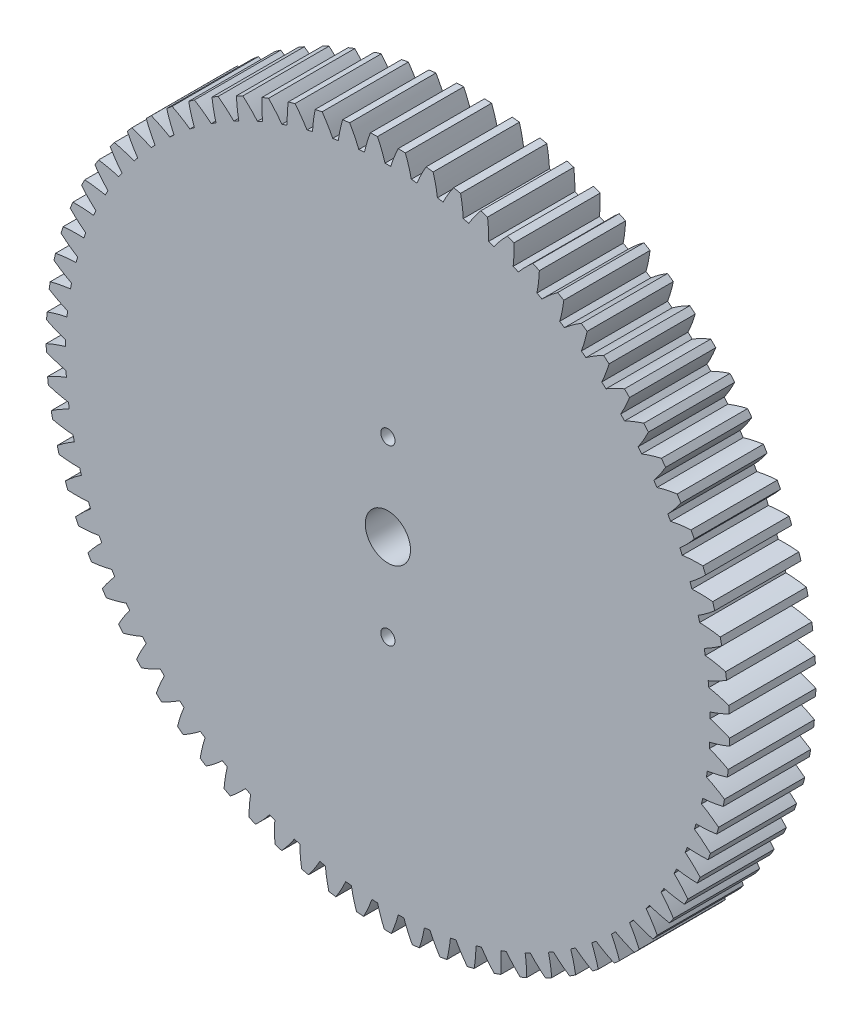
SolidWorks part; units mm, degrees
ref_plane "Front Plane" through (0, 0, 0) normal (0, 0, 1) x (1, 0, 0)
ref_plane "Top Plane" through (0, 0, 0) normal (0, 1, 0) x (1, 0, 0)
ref_plane "Right Plane" through (0, 0, 0) normal (1, 0, 0) x (0, 0, -1)
sketch "Model" plane through (0, 0, 0) normal (0, 0, 1) x (1, 0, 0)
  circle A3 centre (0, 0) radius 2.625
  circle A4 centre (0, 10.05) radius 0.825
  circle A5 centre (0, -10.05) radius 0.825
  arc A311 (-39.5739, 2.0126) -> (-37.3581, 1.0914) centre (-32.524, 15.8446) ccw
  arc A312 (-37.3581, 1.0914) -> (-37.3715, 0.4333) centre (0, 0) ccw
  arc A313 (-37.3715, 0.4333) -> (-39.623, -0.3968) centre (-33.1432, -14.5048) ccw
  arc A314 (-39.623, -0.3968) -> (-39.6062, -1.2197) centre (0, 0) ccw
  arc A315 (-39.6062, -1.2197) -> (-37.3227, -1.9572) centre (-33.7072, 13.1409) ccw
  arc A316 (-37.3227, -1.9572) -> (-37.2825, -2.6143) centre (0, 0) ccw
  arc A317 (-37.2825, -2.6143) -> (-39.4588, -3.6251) centre (-31.8506, -17.158) ccw
  arc A318 (-39.4588, -3.6251) -> (-39.375, -4.4439) centre (0, 0) ccw
  arc A319 (-39.375, -4.4439) -> (-37.039, -4.9929) centre (-34.6662, 10.3497) ccw
  arc A320 (-37.039, -4.9929) -> (-36.9453, -5.6445) centre (0, 0) ccw
  arc A321 (-36.9453, -5.6445) -> (-39.0321, -6.8293) centre (-30.3461, -19.6971) ccw
  arc A322 (-39.0321, -6.8293) -> (-38.8818, -7.6386) centre (0, 0) ccw
  arc A323 (-38.8818, -7.6386) -> (-36.5088, -7.9953) centre (-35.3944, 7.4897) ccw
  arc A324 (-36.5088, -7.9953) -> (-36.3623, -8.6371) centre (0, 0) ccw
  arc A325 (-36.3623, -8.6371) -> (-38.3455, -9.988) centre (-28.6396, -22.105) ccw
  arc A326 (-38.3455, -9.988) -> (-38.1298, -10.7824) centre (0, 0) ccw
  arc A327 (-38.1298, -10.7824) -> (-35.7356, -10.9445) centre (-35.8871, 4.5798) ccw
  arc A328 (-35.7356, -10.9445) -> (-35.5373, -11.5722) centre (0, 0) ccw
  arc A329 (-35.5373, -11.5722) -> (-37.4038, -13.0803) centre (-26.7426, -24.3659) ccw
  arc A330 (-37.4038, -13.0803) -> (-37.124, -13.8544) centre (0, 0) ccw
  arc A331 (-37.124, -13.8544) -> (-34.7246, -13.8209) centre (-36.141, 1.6394) ccw
  arc A332 (-34.7246, -13.8209) -> (-34.4758, -14.4303) centre (0, 0) ccw
  arc A333 (-34.4758, -14.4303) -> (-36.2132, -16.0856) centre (-24.6675, -26.4646) ccw
  arc A334 (-36.2132, -16.0856) -> (-35.8713, -16.8343) centre (0, 0) ccw
  arc A335 (-35.8713, -16.8343) -> (-33.4826, -16.6052) centre (-36.1544, -1.3119) ccw
  arc A336 (-33.4826, -16.6052) -> (-33.1849, -17.1924) centre (0, 0) ccw
  arc A337 (-33.1849, -17.1924) -> (-34.7816, -18.9838) centre (-22.4283, -28.3871) ccw
  arc A338 (-34.7816, -18.9838) -> (-34.3797, -19.7021) centre (0, 0) ccw
  arc A339 (-34.3797, -19.7021) -> (-32.0177, -19.2791) centre (-35.9271, -4.2544) ccw
  arc A340 (-32.0177, -19.2791) -> (-31.6731, -19.8401) centre (0, 0) ccw
  arc A341 (-31.6731, -19.8401) -> (-33.1185, -21.7556) centre (-20.0399, -30.1208) ccw
  arc A342 (-33.1185, -21.7556) -> (-32.6594, -22.4388) centre (0, 0) ccw
  arc A343 (-32.6594, -22.4388) -> (-30.3397, -21.8247) centre (-35.4608, -7.1687) ccw
  arc A344 (-30.3397, -21.8247) -> (-29.9506, -22.3557) centre (0, 0) ccw
  arc A345 (-29.9506, -22.3557) -> (-31.235, -24.3827) centre (-17.5181, -31.654) ccw
  arc A346 (-31.235, -24.3827) -> (-30.7218, -25.0262) centre (0, 0) ccw
  arc A347 (-30.7218, -25.0262) -> (-28.4598, -24.2251) centre (-34.7585, -10.0352) ccw
  arc A348 (-28.4598, -24.2251) -> (-28.0287, -24.7226) centre (0, 0) ccw
  arc A349 (-28.0287, -24.7226) -> (-29.1437, -26.8475) centre (-14.8797, -32.9766) ccw
  arc A350 (-29.1437, -26.8475) -> (-28.5797, -27.4471) centre (0, 0) ccw
  arc A351 (-28.5797, -27.4471) -> (-26.3906, -26.4642) centre (-33.8249, -12.835) ccw
  arc A352 (-26.3906, -26.4642) -> (-25.9204, -26.9249) centre (0, 0) ccw
  arc A353 (-25.9204, -26.9249) -> (-26.8584, -29.1336) centre (-12.1423, -34.0797) ccw
  arc A354 (-26.8584, -29.1336) -> (-26.2474, -29.6852) centre (0, 0) ccw
  arc A355 (-26.2474, -29.6852) -> (-24.1457, -28.5272) centre (-32.6662, -15.5493) ccw
  arc A356 (-24.1457, -28.5272) -> (-23.6395, -28.9481) centre (0, 0) ccw
  arc A357 (-23.6395, -28.9481) -> (-24.3943, -31.2259) centre (-9.3241, -34.956) ccw
  arc A358 (-24.3943, -31.2259) -> (-23.7405, -31.7259) centre (0, 0) ccw
  arc A359 (-23.7405, -31.7259) -> (-21.7401, -30.4004) centre (-31.2901, -18.1602) ccw
  arc A360 (-21.7401, -30.4004) -> (-21.2013, -30.7786) centre (0, 0) ccw
  arc A361 (-21.2013, -30.7786) -> (-21.768, -33.1104) centre (-6.4438, -35.5997) ccw
  arc A362 (-21.768, -33.1104) -> (-21.0755, -33.5554) centre (0, 0) ccw
  arc A363 (-21.0755, -33.5554) -> (-19.1898, -32.0713) centre (-29.7057, -20.6502) ccw
  arc A364 (-19.1898, -32.0713) -> (-18.622, -32.4043) centre (0, 0) ccw
  arc A365 (-18.622, -32.4043) -> (-18.9967, -34.7745) centre (-3.5207, -36.0065) ccw
  arc A366 (-18.9967, -34.7745) -> (-18.2703, -35.1616) centre (0, 0) ccw
  arc A367 (-18.2703, -35.1616) -> (-16.5119, -33.5287) centre (-27.9237, -23.0027) ccw
  arc A368 (-16.5119, -33.5287) -> (-15.9188, -33.8143) centre (0, 0) ccw
  arc A369 (-15.9188, -33.8143) -> (-16.0991, -36.2072) centre (-0.5741, -36.1736) ccw
  arc A370 (-16.0991, -36.2072) -> (-15.3435, -36.5338) centre (0, 0) ccw
  arc A371 (-15.3435, -36.5338) -> (-13.724, -34.763) centre (-25.9559, -25.2022) ccw
  arc A372 (-13.724, -34.763) -> (-13.1096, -34.9993) centre (0, 0) ccw
  arc A373 (-13.1096, -34.9993) -> (-13.0943, -37.3989) centre (2.3763, -36.1) ccw
  arc A374 (-13.0943, -37.3989) -> (-12.3146, -37.6629) centre (0, 0) ccw
  arc A375 (-12.3146, -37.6629) -> (-10.8449, -35.766) centre (-23.8153, -27.234) ccw
  arc A376 (-10.8449, -35.766) -> (-10.2133, -35.9514) centre (0, 0) ccw
  arc A377 (-10.2133, -35.9514) -> (-10.0024, -38.3418) centre (5.3109, -35.7862) ccw
  arc A378 (-10.0024, -38.3418) -> (-9.2038, -38.5413) centre (0, 0) ccw
  arc A379 (-9.2038, -38.5413) -> (-7.8935, -36.5309) centre (-21.5162, -29.0846) ccw
  arc A380 (-7.8935, -36.5309) -> (-7.2489, -36.6643) centre (0, 0) ccw
  arc A381 (-7.2489, -36.6643) -> (-6.8439, -39.0295) centre (8.2101, -35.2343) ccw
  arc A382 (-6.8439, -39.0295) -> (-6.0317, -39.1632) centre (0, 0) ccw
  arc A383 (-6.0317, -39.1632) -> (-4.8897, -37.0528) centre (-19.074, -30.7416) ccw
  arc A384 (-4.8897, -37.0528) -> (-4.2363, -37.1331) centre (0, 0) ccw
  arc A385 (-4.2363, -37.1331) -> (-3.6398, -39.4575) centre (11.0547, -34.4478) ccw
  arc A386 (-3.6398, -39.4575) -> (-2.8194, -39.5246) centre (0, 0) ccw
  arc A387 (-2.8194, -39.5246) -> (-1.8532, -37.328) centre (-16.5048, -32.194) ccw
  arc A388 (-1.8532, -37.328) -> (-1.1955, -37.3549) centre (0, 0) ccw
  arc A389 (-1.1955, -37.3549) -> (-0.4116, -39.6229) centre (13.8257, -33.4321) ccw
  arc A390 (-0.4116, -39.6229) -> (0.4116, -39.6229) centre (0, 0) ccw
  arc A391 (0.4116, -39.6229) -> (1.1955, -37.3549) centre (-13.8257, -33.4321) ccw
  arc A392 (1.1955, -37.3549) -> (1.8532, -37.328) centre (0, 0) ccw
  arc A393 (1.8532, -37.328) -> (2.8194, -39.5246) centre (16.5048, -32.194) ccw
  arc A394 (2.8194, -39.5246) -> (3.6398, -39.4575) centre (0, 0) ccw
  arc A395 (3.6398, -39.4575) -> (4.2363, -37.1331) centre (-11.0547, -34.4478) ccw
  arc A396 (4.2363, -37.1331) -> (4.8897, -37.0528) centre (0, 0) ccw
  arc A397 (4.8897, -37.0528) -> (6.0317, -39.1632) centre (19.074, -30.7416) ccw
  arc A398 (6.0317, -39.1632) -> (6.8439, -39.0295) centre (0, 0) ccw
  arc A399 (6.8439, -39.0295) -> (7.2489, -36.6643) centre (-8.2101, -35.2343) ccw
  arc A400 (7.2489, -36.6643) -> (7.8935, -36.5309) centre (0, 0) ccw
  arc A401 (7.8935, -36.5309) -> (9.2038, -38.5413) centre (21.5162, -29.0846) ccw
  arc A402 (9.2038, -38.5413) -> (10.0024, -38.3418) centre (0, 0) ccw
  arc A403 (10.0024, -38.3418) -> (10.2133, -35.9514) centre (-5.3109, -35.7862) ccw
  arc A404 (10.2133, -35.9514) -> (10.8449, -35.766) centre (0, 0) ccw
  arc A405 (10.8449, -35.766) -> (12.3146, -37.6629) centre (23.8153, -27.234) ccw
  arc A406 (12.3146, -37.6629) -> (13.0943, -37.3989) centre (0, 0) ccw
  arc A407 (13.0943, -37.3989) -> (13.1096, -34.9993) centre (-2.3763, -36.1) ccw
  arc A408 (13.1096, -34.9993) -> (13.724, -34.763) centre (0, 0) ccw
  arc A409 (13.724, -34.763) -> (15.3435, -36.5338) centre (25.9559, -25.2022) ccw
  arc A410 (15.3435, -36.5338) -> (16.0991, -36.2072) centre (0, 0) ccw
  arc A411 (16.0991, -36.2072) -> (15.9188, -33.8143) centre (0.5741, -36.1736) ccw
  arc A412 (15.9188, -33.8143) -> (16.5119, -33.5287) centre (0, 0) ccw
  arc A413 (16.5119, -33.5287) -> (18.2703, -35.1616) centre (27.9237, -23.0027) ccw
  arc A414 (18.2703, -35.1616) -> (18.9967, -34.7745) centre (0, 0) ccw
  arc A415 (18.9967, -34.7745) -> (18.622, -32.4043) centre (3.5207, -36.0065) ccw
  arc A416 (18.622, -32.4043) -> (19.1898, -32.0713) centre (0, 0) ccw
  arc A417 (19.1898, -32.0713) -> (21.0755, -33.5554) centre (29.7057, -20.6502) ccw
  arc A418 (21.0755, -33.5554) -> (21.768, -33.1104) centre (0, 0) ccw
  arc A419 (21.768, -33.1104) -> (21.2013, -30.7786) centre (6.4438, -35.5997) ccw
  arc A420 (21.2013, -30.7786) -> (21.7401, -30.4004) centre (0, 0) ccw
  arc A421 (21.7401, -30.4004) -> (23.7405, -31.7259) centre (31.2901, -18.1602) ccw
  arc A422 (23.7405, -31.7259) -> (24.3943, -31.2259) centre (0, 0) ccw
  arc A423 (24.3943, -31.2259) -> (23.6395, -28.9481) centre (9.3241, -34.956) ccw
  arc A424 (23.6395, -28.9481) -> (24.1457, -28.5272) centre (0, 0) ccw
  arc A425 (24.1457, -28.5272) -> (26.2474, -29.6852) centre (32.6662, -15.5493) ccw
  arc A426 (26.2474, -29.6852) -> (26.8584, -29.1336) centre (0, 0) ccw
  arc A427 (26.8584, -29.1336) -> (25.9204, -26.9249) centre (12.1423, -34.0797) ccw
  arc A428 (25.9204, -26.9249) -> (26.3906, -26.4642) centre (0, 0) ccw
  arc A429 (26.3906, -26.4642) -> (28.5797, -27.4471) centre (33.8249, -12.835) ccw
  arc A430 (28.5797, -27.4471) -> (29.1437, -26.8475) centre (0, 0) ccw
  arc A431 (29.1437, -26.8475) -> (28.0287, -24.7226) centre (14.8797, -32.9766) ccw
  arc A432 (28.0287, -24.7226) -> (28.4598, -24.2251) centre (0, 0) ccw
  arc A433 (28.4598, -24.2251) -> (30.7218, -25.0262) centre (34.7585, -10.0352) ccw
  arc A434 (30.7218, -25.0262) -> (31.235, -24.3827) centre (0, 0) ccw
  arc A435 (31.235, -24.3827) -> (29.9506, -22.3557) centre (17.5181, -31.654) ccw
  arc A436 (29.9506, -22.3557) -> (30.3397, -21.8247) centre (0, 0) ccw
  arc A437 (30.3397, -21.8247) -> (32.6594, -22.4388) centre (35.4608, -7.1687) ccw
  arc A438 (32.6594, -22.4388) -> (33.1185, -21.7556) centre (0, 0) ccw
  arc A439 (33.1185, -21.7556) -> (31.6731, -19.8401) centre (20.0399, -30.1208) ccw
  arc A440 (31.6731, -19.8401) -> (32.0177, -19.2791) centre (0, 0) ccw
  arc A441 (32.0177, -19.2791) -> (34.3797, -19.7021) centre (35.9271, -4.2544) ccw
  arc A442 (34.3797, -19.7021) -> (34.7816, -18.9838) centre (0, 0) ccw
  arc A443 (34.7816, -18.9838) -> (33.1849, -17.1924) centre (22.4283, -28.3871) ccw
  arc A444 (33.1849, -17.1924) -> (33.4826, -16.6052) centre (0, 0) ccw
  arc A445 (33.4826, -16.6052) -> (35.8713, -16.8343) centre (36.1544, -1.3119) ccw
  arc A446 (35.8713, -16.8343) -> (36.2132, -16.0856) centre (0, 0) ccw
  arc A447 (36.2132, -16.0856) -> (34.4758, -14.4303) centre (24.6675, -26.4646) ccw
  arc A448 (34.4758, -14.4303) -> (34.7246, -13.8209) centre (0, 0) ccw
  arc A449 (34.7246, -13.8209) -> (37.124, -13.8544) centre (36.141, 1.6394) ccw
  arc A450 (37.124, -13.8544) -> (37.4038, -13.0803) centre (0, 0) ccw
  arc A451 (37.4038, -13.0803) -> (35.5373, -11.5722) centre (26.7426, -24.3659) ccw
  arc A452 (35.5373, -11.5722) -> (35.7356, -10.9445) centre (0, 0) ccw
  arc A453 (35.7356, -10.9445) -> (38.1298, -10.7824) centre (35.8871, 4.5798) ccw
  arc A454 (38.1298, -10.7824) -> (38.3455, -9.988) centre (0, 0) ccw
  arc A455 (38.3455, -9.988) -> (36.3623, -8.6371) centre (28.6396, -22.105) ccw
  arc A456 (36.3623, -8.6371) -> (36.5088, -7.9953) centre (0, 0) ccw
  arc A457 (36.5088, -7.9953) -> (38.8818, -7.6386) centre (35.3944, 7.4897) ccw
  arc A458 (38.8818, -7.6386) -> (39.0321, -6.8293) centre (0, 0) ccw
  arc A459 (39.0321, -6.8293) -> (36.9453, -5.6445) centre (30.3461, -19.6971) ccw
  arc A460 (36.9453, -5.6445) -> (37.039, -4.9929) centre (0, 0) ccw
  arc A461 (37.039, -4.9929) -> (39.375, -4.4439) centre (34.6662, 10.3497) ccw
  arc A462 (39.375, -4.4439) -> (39.4588, -3.6251) centre (0, 0) ccw
  arc A463 (39.4588, -3.6251) -> (37.2825, -2.6143) centre (31.8506, -17.158) ccw
  arc A464 (37.2825, -2.6143) -> (37.3227, -1.9572) centre (0, 0) ccw
  arc A465 (37.3227, -1.9572) -> (39.6062, -1.2197) centre (33.7072, 13.1409) ccw
  arc A466 (39.6062, -1.2197) -> (39.623, -0.3968) centre (0, 0) ccw
  arc A467 (39.623, -0.3968) -> (37.3715, 0.4333) centre (33.1432, -14.5048) ccw
  arc A468 (37.3715, 0.4333) -> (37.3581, 1.0914) centre (0, 0) ccw
  arc A469 (37.3581, 1.0914) -> (39.5739, 2.0126) centre (32.524, 15.8446) ccw
  arc A470 (39.5739, 2.0126) -> (39.5235, 2.8342) centre (0, 0) ccw
  arc A471 (39.5235, 2.8342) -> (37.2118, 3.478) centre (34.2152, -11.7551) ccw
  arc A472 (37.2118, 3.478) -> (37.1448, 4.1328) centre (0, 0) ccw
  arc A473 (37.1448, 4.1328) -> (39.2781, 5.2315) centre (31.1243, 18.4429) ccw
  arc A474 (39.2781, 5.2315) -> (39.161, 6.0463) centre (0, 0) ccw
  arc A475 (39.161, 6.0463) -> (36.8045, 6.4995) centre (35.0595, -8.9271) ccw
  arc A476 (36.8045, 6.4995) -> (36.6843, 7.1467) centre (0, 0) ccw
  arc A477 (36.6843, 7.1467) -> (38.721, 8.4157) centre (29.5174, 20.9185) ccw
  arc A478 (38.721, 8.4157) -> (38.5379, 9.2182) centre (0, 0) ccw
  arc A479 (38.5379, 9.2182) -> (36.1523, 9.4778) centre (35.6705, -6.0397) ccw
  arc A480 (36.1523, 9.4778) -> (35.9797, 10.113) centre (0, 0) ccw
  arc A481 (35.9797, 10.113) -> (37.9062, 11.5438) centre (27.7142, 23.2548) ccw
  arc A482 (37.9062, 11.5438) -> (37.6583, 12.3287) centre (0, 0) ccw
  arc A483 (37.6583, 12.3287) -> (35.2595, 12.393) centre (36.0441, -3.1122) ccw
  arc A484 (35.2595, 12.393) -> (35.0357, 13.0121) centre (0, 0) ccw
  arc A485 (35.0357, 13.0121) -> (36.8392, 14.5951) centre (25.7265, 25.4364) ccw
  arc A486 (36.8392, 14.5951) -> (36.5281, 15.3572) centre (0, 0) ccw
  arc A487 (36.5281, 15.3572) -> (34.132, 15.2257) centre (36.1778, -0.1639) ccw
  arc A488 (34.132, 15.2257) -> (33.8585, 15.8245) centre (0, 0) ccw
  arc A489 (33.8585, 15.8245) -> (35.5269, 17.5493) centre (23.5676, 27.4487) ccw
  arc A490 (35.5269, 17.5493) -> (35.1548, 18.2834) centre (0, 0) ccw
  arc A491 (35.1548, 18.2834) -> (32.7774, 17.9571) centre (36.0708, 2.7855) ccw
  arc A492 (32.7774, 17.9571) -> (32.456, 18.5316) centre (0, 0) ccw
  arc A493 (32.456, 18.5316) -> (33.9783, 20.3866) centre (21.2518, 29.2783) ccw
  arc A494 (33.9783, 20.3866) -> (33.5475, 21.088) centre (0, 0) ccw
  arc A495 (33.5475, 21.088) -> (31.2047, 20.569) centre (35.7237, 5.7163) ccw
  arc A496 (31.2047, 20.569) -> (30.8375, 21.1154) centre (0, 0) ccw
  arc A497 (30.8375, 21.1154) -> (32.2035, 23.0884) centre (18.7946, 30.9131) ccw
  arc A498 (32.2035, 23.0884) -> (31.717, 23.7523) centre (0, 0) ccw
  arc A499 (31.717, 23.7523) -> (29.4243, 23.0441) centre (35.1389, 8.6091) ccw
  arc A500 (29.4243, 23.0441) -> (29.0138, 23.5587) centre (0, 0) ccw
  arc A501 (29.0138, 23.5587) -> (30.2145, 25.6364) centre (16.2124, 32.3422) ccw
  arc A502 (30.2145, 25.6364) -> (29.6754, 26.2585) centre (0, 0) ccw
  arc A503 (29.6754, 26.2585) -> (27.448, 25.3657) centre (34.3203, 11.4446) ccw
  arc A504 (27.448, 25.3657) -> (26.997, 25.8452) centre (0, 0) ccw
  arc A505 (26.997, 25.8452) -> (28.0243, 28.0139) centre (13.5223, 33.556) ccw
  arc A506 (28.0243, 28.0139) -> (27.4364, 28.5899) centre (0, 0) ccw
  arc A507 (27.4364, 28.5899) -> (25.2892, 27.5186) centre (33.2732, 14.2039) ccw
  arc A508 (25.2892, 27.5186) -> (24.8006, 27.9598) centre (0, 0) ccw
  arc A509 (24.8006, 27.9598) -> (25.6477, 30.2049) centre (10.7421, 34.5466) ccw
  arc A510 (25.6477, 30.2049) -> (25.0148, 30.7311) centre (0, 0) ccw
  arc A511 (25.0148, 30.7311) -> (22.962, 29.4883) centre (32.0048, 16.8688) ccw
  arc A512 (22.962, 29.4883) -> (22.4391, 29.8882) centre (0, 0) ccw
  arc A513 (22.4391, 29.8882) -> (23.1004, 32.1949) centre (7.8905, 35.3072) ccw
  arc A514 (23.1004, 32.1949) -> (22.4266, 32.6678) centre (0, 0) ccw
  arc A515 (22.4266, 32.6678) -> (20.482, 31.2618) centre (30.5233, 19.4213) ccw
  arc A516 (20.482, 31.2618) -> (19.9282, 31.6177) centre (0, 0) ccw
  arc A517 (19.9282, 31.6177) -> (20.3993, 33.9707) centre (4.9864, 35.8329) ccw
  arc A518 (20.3993, 33.9707) -> (19.6893, 34.3871) centre (0, 0) ccw
  arc A519 (19.6893, 34.3871) -> (17.8657, 32.8273) centre (28.8387, 21.8446) ccw
  arc A520 (17.8657, 32.8273) -> (17.2848, 33.1369) centre (0, 0) ccw
  arc A521 (17.2848, 33.1369) -> (17.5625, 35.5204) centre (2.0491, 36.1201) ccw
  arc A522 (17.5625, 35.5204) -> (16.8209, 35.8775) centre (0, 0) ccw
  arc A523 (16.8209, 35.8775) -> (15.1306, 34.1743) centre (26.9622, 24.1226) ccw
  arc A524 (15.1306, 34.1743) -> (14.5263, 34.4355) centre (0, 0) ccw
  arc A525 (14.5263, 34.4355) -> (14.6088, 36.8337) centre (-0.9018, 36.1669) ccw
  arc A526 (14.6088, 36.8337) -> (13.8406, 37.1292) centre (0, 0) ccw
  arc A527 (13.8406, 37.1292) -> (12.2947, 35.2939) centre (24.9063, 26.24) ccw
  arc A528 (12.2947, 35.2939) -> (11.6712, 35.5049) centre (0, 0) ccw
  arc A529 (11.6712, 35.5049) -> (11.5579, 37.9019) centre (-3.8468, 35.9731) ccw
  arc A530 (11.5579, 37.9019) -> (10.7682, 38.1338) centre (0, 0) ccw
  arc A531 (10.7682, 38.1338) -> (9.377, 36.1786) centre (22.6846, 28.1828) ccw
  arc A532 (9.377, 36.1786) -> (8.7384, 36.3381) centre (0, 0) ccw
  arc A533 (8.7384, 36.3381) -> (8.4301, 38.7179) centre (-6.7661, 35.5398) ccw
  arc A534 (8.4301, 38.7179) -> (7.6241, 38.8846) centre (0, 0) ccw
  arc A535 (7.6241, 38.8846) -> (6.3969, 36.8225) centre (20.312, 29.938) ccw
  arc A536 (6.3969, 36.8225) -> (5.7474, 36.9294) centre (0, 0) ccw
  arc A537 (5.7474, 36.9294) -> (5.2462, 39.2762) centre (-9.6404, 34.8701) ccw
  arc A538 (5.2462, 39.2762) -> (4.4292, 39.3767) centre (0, 0) ccw
  arc A539 (4.4292, 39.3767) -> (3.3743, 37.2214) centre (17.8042, 31.494) ccw
  arc A540 (3.3743, 37.2214) -> (2.7182, 37.275) centre (0, 0) ccw
  arc A541 (2.7182, 37.275) -> (2.0274, 39.5731) centre (-12.4506, 33.9683) ccw
  arc A542 (2.0274, 39.5731) -> (1.2049, 39.6067) centre (0, 0) ccw
  arc A543 (1.2049, 39.6067) -> (0.3291, 37.3726) centre (15.1779, 32.8404) ccw
  arc A544 (0.3291, 37.3726) -> (-0.3291, 37.3726) centre (0, 0) ccw
  arc A545 (-0.3291, 37.3726) -> (-1.2049, 39.6067) centre (-15.1779, 32.8404) ccw
  arc A546 (-1.2049, 39.6067) -> (-2.0274, 39.5731) centre (0, 0) ccw
  arc A547 (-2.0274, 39.5731) -> (-2.7182, 37.275) centre (12.4506, 33.9683) ccw
  arc A548 (-2.7182, 37.275) -> (-3.3743, 37.2214) centre (0, 0) ccw
  arc A549 (-3.3743, 37.2214) -> (-4.4292, 39.3767) centre (-17.8042, 31.494) ccw
  arc A550 (-4.4292, 39.3767) -> (-5.2462, 39.2762) centre (0, 0) ccw
  arc A551 (-5.2462, 39.2762) -> (-5.7474, 36.9294) centre (9.6404, 34.8701) ccw
  arc A552 (-5.7474, 36.9294) -> (-6.3969, 36.8225) centre (0, 0) ccw
  arc A553 (-6.3969, 36.8225) -> (-7.6241, 38.8846) centre (-20.312, 29.938) ccw
  arc A554 (-7.6241, 38.8846) -> (-8.4301, 38.7179) centre (0, 0) ccw
  arc A555 (-8.4301, 38.7179) -> (-8.7384, 36.3381) centre (6.7661, 35.5398) ccw
  arc A556 (-8.7384, 36.3381) -> (-9.377, 36.1786) centre (0, 0) ccw
  arc A557 (-9.377, 36.1786) -> (-10.7682, 38.1338) centre (-22.6846, 28.1828) ccw
  arc A558 (-10.7682, 38.1338) -> (-11.5579, 37.9019) centre (0, 0) ccw
  arc A559 (-11.5579, 37.9019) -> (-11.6712, 35.5049) centre (3.8468, 35.9731) ccw
  arc A560 (-11.6712, 35.5049) -> (-12.2947, 35.2939) centre (0, 0) ccw
  arc A561 (-12.2947, 35.2939) -> (-13.8406, 37.1292) centre (-24.9063, 26.24) ccw
  arc A562 (-13.8406, 37.1292) -> (-14.6088, 36.8337) centre (0, 0) ccw
  arc A563 (-14.6088, 36.8337) -> (-14.5263, 34.4355) centre (0.9018, 36.1669) ccw
  arc A564 (-14.5263, 34.4355) -> (-15.1306, 34.1743) centre (0, 0) ccw
  arc A565 (-15.1306, 34.1743) -> (-16.8209, 35.8775) centre (-26.9622, 24.1226) ccw
  arc A566 (-16.8209, 35.8775) -> (-17.5625, 35.5204) centre (0, 0) ccw
  arc A567 (-17.5625, 35.5204) -> (-17.2848, 33.1369) centre (-2.0491, 36.1201) ccw
  arc A568 (-17.2848, 33.1369) -> (-17.8657, 32.8273) centre (0, 0) ccw
  arc A569 (-17.8657, 32.8273) -> (-19.6893, 34.3871) centre (-28.8387, 21.8446) ccw
  arc A570 (-19.6893, 34.3871) -> (-20.3993, 33.9707) centre (0, 0) ccw
  arc A571 (-20.3993, 33.9707) -> (-19.9282, 31.6177) centre (-4.9864, 35.8329) ccw
  arc A572 (-19.9282, 31.6177) -> (-20.482, 31.2618) centre (0, 0) ccw
  arc A573 (-20.482, 31.2618) -> (-22.4266, 32.6678) centre (-30.5233, 19.4213) ccw
  arc A574 (-22.4266, 32.6678) -> (-23.1004, 32.1949) centre (0, 0) ccw
  arc A575 (-23.1004, 32.1949) -> (-22.4391, 29.8882) centre (-7.8905, 35.3072) ccw
  arc A576 (-22.4391, 29.8882) -> (-22.962, 29.4883) centre (0, 0) ccw
  arc A577 (-22.962, 29.4883) -> (-25.0148, 30.7311) centre (-32.0048, 16.8688) ccw
  arc A578 (-25.0148, 30.7311) -> (-25.6477, 30.2049) centre (0, 0) ccw
  arc A579 (-25.6477, 30.2049) -> (-24.8006, 27.9598) centre (-10.7421, 34.5466) ccw
  arc A580 (-24.8006, 27.9598) -> (-25.2892, 27.5186) centre (0, 0) ccw
  arc A581 (-25.2892, 27.5186) -> (-27.4364, 28.5899) centre (-33.2732, 14.2039) ccw
  arc A582 (-27.4364, 28.5899) -> (-28.0243, 28.0139) centre (0, 0) ccw
  arc A583 (-28.0243, 28.0139) -> (-26.997, 25.8452) centre (-13.5223, 33.556) ccw
  arc A584 (-26.997, 25.8452) -> (-27.448, 25.3657) centre (0, 0) ccw
  arc A585 (-27.448, 25.3657) -> (-29.6754, 26.2585) centre (-34.3203, 11.4446) ccw
  arc A586 (-29.6754, 26.2585) -> (-30.2145, 25.6364) centre (0, 0) ccw
  arc A587 (-30.2145, 25.6364) -> (-29.0138, 23.5587) centre (-16.2124, 32.3422) ccw
  arc A588 (-29.0138, 23.5587) -> (-29.4243, 23.0441) centre (0, 0) ccw
  arc A589 (-29.4243, 23.0441) -> (-31.717, 23.7523) centre (-35.1389, 8.6091) ccw
  arc A590 (-31.717, 23.7523) -> (-32.2035, 23.0884) centre (0, 0) ccw
  arc A591 (-32.2035, 23.0884) -> (-30.8375, 21.1154) centre (-18.7946, 30.9131) ccw
  arc A592 (-30.8375, 21.1154) -> (-31.2047, 20.569) centre (0, 0) ccw
  arc A593 (-31.2047, 20.569) -> (-33.5475, 21.088) centre (-35.7237, 5.7163) ccw
  arc A594 (-33.5475, 21.088) -> (-33.9783, 20.3866) centre (0, 0) ccw
  arc A595 (-33.9783, 20.3866) -> (-32.456, 18.5316) centre (-21.2518, 29.2783) ccw
  arc A596 (-32.456, 18.5316) -> (-32.7774, 17.9571) centre (0, 0) ccw
  arc A597 (-32.7774, 17.9571) -> (-35.1548, 18.2834) centre (-36.0708, 2.7855) ccw
  arc A598 (-35.1548, 18.2834) -> (-35.5269, 17.5493) centre (0, 0) ccw
  arc A599 (-35.5269, 17.5493) -> (-33.8585, 15.8245) centre (-23.5676, 27.4487) ccw
  arc A600 (-33.8585, 15.8245) -> (-34.132, 15.2257) centre (0, 0) ccw
  arc A601 (-34.132, 15.2257) -> (-36.5281, 15.3572) centre (-36.1778, -0.1639) ccw
  arc A602 (-36.5281, 15.3572) -> (-36.8392, 14.5951) centre (0, 0) ccw
  arc A603 (-36.8392, 14.5951) -> (-35.0357, 13.0121) centre (-25.7265, 25.4364) ccw
  arc A604 (-35.0357, 13.0121) -> (-35.2595, 12.393) centre (0, 0) ccw
  arc A605 (-35.2595, 12.393) -> (-37.6583, 12.3287) centre (-36.0441, -3.1122) ccw
  arc A606 (-37.6583, 12.3287) -> (-37.9062, 11.5438) centre (0, 0) ccw
  arc A607 (-37.9062, 11.5438) -> (-35.9797, 10.113) centre (-27.7142, 23.2548) ccw
  arc A608 (-35.9797, 10.113) -> (-36.1523, 9.4778) centre (0, 0) ccw
  arc A609 (-36.1523, 9.4778) -> (-38.5379, 9.2182) centre (-35.6705, -6.0397) ccw
  arc A610 (-38.5379, 9.2182) -> (-38.721, 8.4157) centre (0, 0) ccw
  arc A611 (-38.721, 8.4157) -> (-36.6843, 7.1467) centre (-29.5174, 20.9185) ccw
  arc A612 (-36.6843, 7.1467) -> (-36.8045, 6.4995) centre (0, 0) ccw
  arc A613 (-36.8045, 6.4995) -> (-39.161, 6.0463) centre (-35.0595, -8.9271) ccw
  arc A614 (-39.161, 6.0463) -> (-39.2781, 5.2315) centre (0, 0) ccw
  arc A615 (-39.2781, 5.2315) -> (-37.1448, 4.1328) centre (-31.1243, 18.4429) ccw
  arc A616 (-37.1448, 4.1328) -> (-37.2118, 3.478) centre (0, 0) ccw
  arc A617 (-37.2118, 3.478) -> (-39.5235, 2.8342) centre (-34.2152, -11.7551) ccw
  arc A618 (-39.5235, 2.8342) -> (-39.5739, 2.0126) centre (0, 0) ccw
extrude "Boss-Extrude2" add sketch "Model" along normal blind 10
